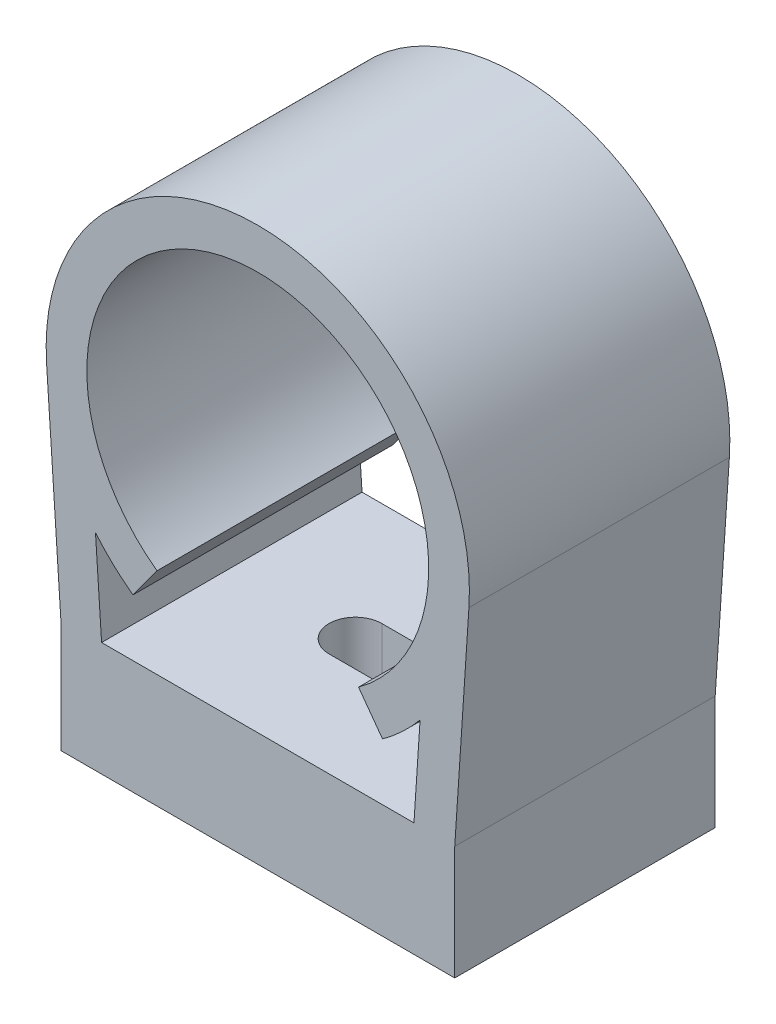
SolidWorks part; units mm, degrees
ref_plane "Front Plane" through (0, 0, 0) normal (0, 0, 1) x (1, 0, 0)
ref_plane "Top Plane" through (0, 0, 0) normal (0, 1, 0) x (1, 0, 0)
ref_plane "Right Plane" through (0, 0, 0) normal (1, 0, 0) x (0, 0, -1)
sketch "Sketch1" plane through (0, 0, 0) normal (0, 0, 1) x (1, 0, 0)
  line L0 (15.367, 0) -> (15.367, 26.67) construction
  line L1 (0, 0) -> (30.734, 0)
  line L2 (0, 0) -> (0, 8.89)
  line L3 (3.182, 8.89) -> (27.552, 8.89)
  line L4 (30.734, 0) -> (30.734, 8.89)
  line L5 (0, 8.89) -> (-1.1068, 25.5774)
  line L6 (30.734, 8.89) -> (31.8408, 25.5774)
  line L7 (3.182, 8.89) -> (2.7055, 16.0745)
  line L8 (27.552, 8.89) -> (28.0285, 16.0745)
  line L10 (5.6326, 13.335) -> (7.5046, 15.8994)
  line L11 (25.1014, 13.335) -> (23.2294, 15.8994)
  arc A0 (23.2294, 15.8994) -> (7.5046, 15.8994) centre (15.367, 26.67) ccw
  arc A1 (31.8408, 25.5774) -> (-1.1068, 25.5774) centre (15.367, 26.67) ccw
  arc A2 (2.7055, 16.0745) -> (5.6326, 13.335) centre (15.367, 26.67) ccw
  arc A3 (25.1014, 13.335) -> (28.0285, 16.0745) centre (15.367, 26.67) ccw
  point P17 (15.367, 13.335)
  dimension "D2" = 26.67
  dimension "D5" = 3.175
  dimension "D1" = 26.67
  dimension "D3" = 8.89
  dimension "D4" = 30.734
  dimension "D6" = 3.175
  dimension "D7" = 3.175
extrude "Boss-Extrude1" add sketch "Sketch1" along normal blind 20.32
sketch "Sketch2" plane through (0, 0, 0) normal (0, -1, 0) x (1, 0, 0)
  line L0 (0, 20.32) -> (30.734, 0) construction
  line L1 (12.827, 10.16) -> (17.907, 10.16) construction
  line L2 (12.827, 12.2174) -> (17.907, 12.2174)
  line L3 (12.827, 8.1026) -> (17.907, 8.1026)
  arc A0 (12.827, 12.2174) -> (12.827, 8.1026) centre (12.827, 10.16) ccw
  arc A1 (17.907, 8.1026) -> (17.907, 12.2174) centre (17.907, 10.16) ccw
  point P6 (15.367, 10.16)
  dimension "D2" = 2.0574
  dimension "D1" = 5.08
extrude "Cut-Extrude1" cut sketch "Sketch2" against normal up to next
